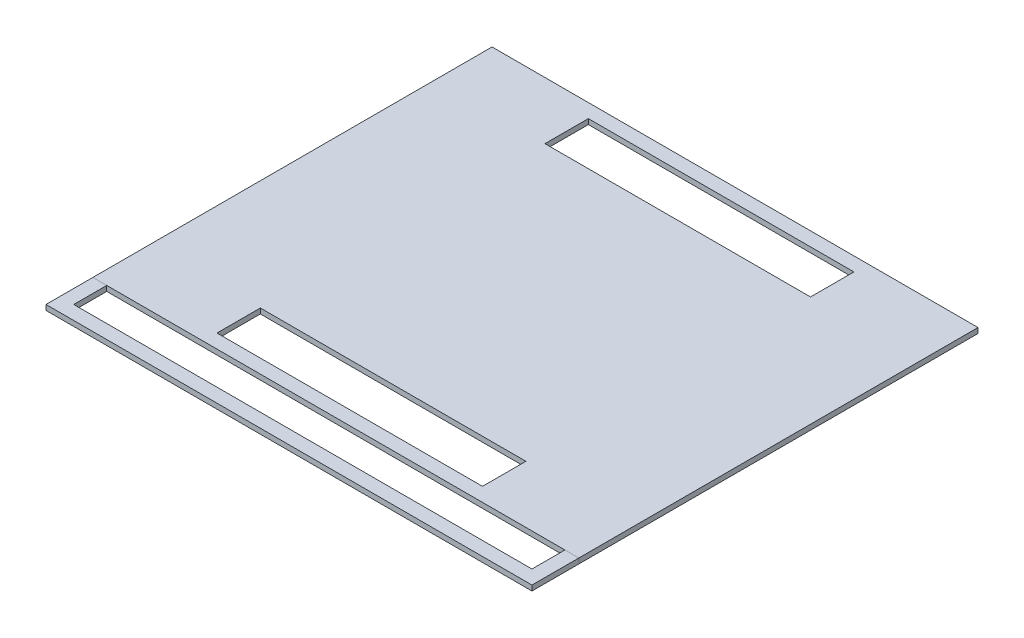
SolidWorks part; units mm, degrees
ref_plane "Front Plane" through (0, 0, 0) normal (0, 0, 1) x (1, 0, 0)
ref_plane "Top Plane" through (0, 0, 0) normal (0, 1, 0) x (1, 0, 0)
ref_plane "Right Plane" through (0, 0, 0) normal (1, 0, 0) x (0, 0, -1)
sketch "Sketch1" plane through (0, 0, 0) normal (0, 1, 0) x (1, 0, 0)
  line L1 (0, 0) -> (-280, 0)
  line L2 (0, 0) -> (0, 230)
  line L3 (0, 230) -> (-280, 230)
  line L4 (-280, 0) -> (-280, 230)
  dimension "D1" = 280
  dimension "D2" = 230
extrude "Boss-Extrude1" add sketch "Sketch1" along normal blind 3
sketch "Sketch4" plane through (0, 3, 0) normal (0, 1, 0) x (1, 0, 0)
  line L0 (-140, 230) -> (-140, 222) construction
  line L1 (0, 230) -> (-280, 230) construction
  line L2 (-140, 222) -> (-216.5, 222) construction
  line L3 (-140, 222) -> (-63.5, 222) construction
  line L4 (-63.5, 222) -> (-63.5, 197) construction
  line L5 (-140, 0) -> (-140, 8) construction
  line L6 (-63.5, 222) -> (-216.5, 222)
  line L7 (-63.5, 222) -> (-63.5, 197)
  line L8 (-63.5, 197) -> (-216.5, 197)
  line L9 (-216.5, 222) -> (-216.5, 197)
  line L10 (-280, 0) -> (0, 0) construction
  line L12 (-216.5, 8) -> (-63.5, 8)
  line L13 (-216.5, 8) -> (-216.5, 33)
  line L14 (-216.5, 33) -> (-63.5, 33)
  line L15 (-63.5, 8) -> (-63.5, 33)
  dimension "D1" = 8
  dimension "D2" = 76.5
  dimension "D3" = 76.5
  dimension "D4" = 25
  dimension "D5" = 8
  dimension "D6" = 25
extrude "Cut-Extrude2" cut sketch "Sketch4" against normal through all
sketch "Sketch5" plane through (0, 3, 0) normal (0, 1, 0) x (1, 0, 0)
  line L0 (0, 230) -> (0, -27) construction
  line L1 (-280, 0) -> (0, 0)
  line L2 (-280, 0) -> (-280, -27)
  line L3 (-280, -27) -> (0, -27)
  line L4 (0, 0) -> (0, -27)
  dimension "D1" = 27
  dimension "D2" = 257
extrude "Boss-Extrude2" add sketch "Sketch5" against normal blind 3 separate body
sketch "Sketch6" plane through (0, 0, 0) normal (0, -1, 0) x (1, 0, 0)
  line L0 (-280, -230) -> (-280, 27) construction
  dimension "D1" = 257
sketch "Sketch7" plane through (0, 3, 0) normal (0, 1, 0) x (1, 0, 0)
  line L1 (-272, 0) -> (-8, 0)
  line L5 (-272, -19) -> (-8, -19)
  line L8 (-272, -8) -> (-8, -8) construction
  line L9 (-272, -8) -> (-272, -19) construction
  line L10 (-8, -8) -> (-8, -19) construction
  line L11 (-8, 0) -> (0, 0) construction
  line L13 (-272, -19) -> (-272, 0)
  line L15 (-8, -19) -> (-8, 0)
  line L16 (-280, 0) -> (-280, -27) construction
  line L17 (-280, 0) -> (0, 0) construction
  line L18 (-280, -27) -> (0, -27) construction
  line L19 (0, 0) -> (0, -27) construction
  line L20 (-272, 0) -> (-280, 0) construction
  dimension "D1" = 8
extrude "Cut-Extrude4" cut sketch "Sketch7" against normal through all
